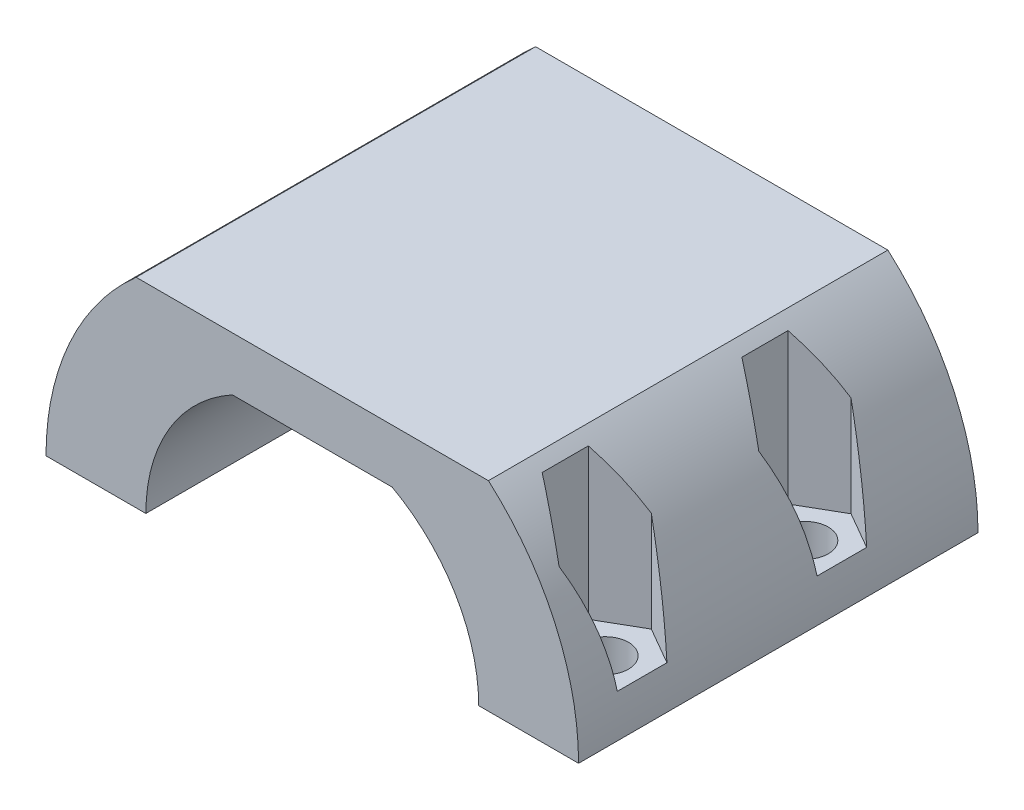
SolidWorks part; units mm, degrees
ref_plane "Front Plane" through (0, 0, 0) normal (0, 0, 1) x (1, 0, 0)
ref_plane "Top Plane" through (0, 0, 0) normal (0, 1, 0) x (1, 0, 0)
ref_plane "Right Plane" through (0, 0, 0) normal (1, 0, 0) x (0, 0, -1)
sketch "Sketch1" plane through (0, 0, 0) normal (0, 0, 1) x (1, 0, 0)
  line L0 (-20, 0) -> (-12.5, 0)
  line L1 (12.5, 0) -> (20, 0)
  line L2 (-6, 10.9659) -> (6, 10.9659)
  arc A0 (12.5, 0) -> (6, 10.9659) centre (0, 0) ccw
  arc A1 (20, 0) -> (-20, 0) centre (0, 0) ccw
  arc A2 (-6, 10.9659) -> (-12.5, 0) centre (0, 0) ccw
  dimension "D1" = 25
  dimension "D2" = 40
  dimension "D3" = 12
extrude "Boss-Extrude1" add sketch "Sketch1" along normal blind 30
sketch "Sketch2" plane through (0, 0, 0) normal (0, 1, 0) x (1, 0, 0)
  line L0 (0, 0) -> (0, -30) construction
  line L1 (-17, -25) -> (17, -25) construction
  line L2 (-17, -25) -> (-17, -10) construction
  line L3 (-17, -10) -> (17, -10) construction
  line L4 (17, -25) -> (17, -10) construction
  line L5 (-17, -25) -> (17, -10) construction
  line L6 (-17, -10) -> (17, -25) construction
  line L7 (-20, -30) -> (20, -30) construction
  line L8 (0, -30) -> (0, 0) construction
  circle A0 centre (-17, -10) radius 1.75
  circle A1 centre (17, -10) radius 1.75
  circle A2 centre (17, -25) radius 1.75
  circle A3 centre (-17, -25) radius 1.75
  point P0 (0, -17.5)
  dimension "D3" = 3.5
  dimension "D1" = 15
  dimension "D2" = 34
  dimension "D4" = 5
extrude "Cut-Extrude2" cut sketch "Sketch2" along normal through all
ref_plane "Plane1" through (0, 3, 0) normal (0, 1, 0) x (1, 0, 0)
sketch "Sketch4" plane through (0, 3, 0) normal (0, 1, 0) x (1, 0, 0)
  line L1 (-17, -6.5359) -> (-20, -8.2679)
  line L2 (-20, -8.2679) -> (-20, -11.7321)
  line L3 (-20, -11.7321) -> (-17, -13.4641)
  line L4 (-17, -13.4641) -> (-14, -11.7321)
  line L5 (-14, -11.7321) -> (-14, -8.2679)
  line L6 (-14, -8.2679) -> (-17, -6.5359)
  line L7 (-17, -21.5359) -> (-20, -23.2679)
  line L8 (-20, -23.2679) -> (-20, -26.7321)
  line L9 (-20, -26.7321) -> (-17, -28.4641)
  line L10 (-17, -28.4641) -> (-14, -26.7321)
  line L11 (-14, -26.7321) -> (-14, -23.2679)
  line L12 (-14, -23.2679) -> (-17, -21.5359)
  line L13 (17, -21.5359) -> (14, -23.2679)
  line L14 (14, -23.2679) -> (14, -26.7321)
  line L15 (14, -26.7321) -> (17, -28.4641)
  line L16 (17, -28.4641) -> (20, -26.7321)
  line L17 (20, -26.7321) -> (20, -23.2679)
  line L18 (20, -23.2679) -> (17, -21.5359)
  line L19 (14, -8.2679) -> (14, -11.7321)
  line L20 (14, -11.7321) -> (17, -13.4641)
  line L21 (17, -13.4641) -> (20, -11.7321)
  line L22 (20, -11.7321) -> (20, -8.2679)
  line L23 (20, -8.2679) -> (17, -6.5359)
  line L24 (17, -6.5359) -> (14, -8.2679)
  circle A1 centre (-17, -10) radius 3 construction
  circle A4 centre (-17, -25) radius 3 construction
  circle A6 centre (17, -25) radius 3 construction
  circle A7 centre (17, -10) radius 3 construction
  dimension "D1" = 6
extrude "Cut-Extrude3" cut sketch "Sketch4" along normal through all
sketch "Sketch5" plane through (0, 0, 30) normal (0, 0, 1) x (1, 0, 0)
  line L1 (-16.8059, 25) -> (16.8059, 25)
  line L2 (-16.8059, 25) -> (-16.8059, 15)
  line L3 (-16.8059, 15) -> (16.8059, 15)
  line L4 (16.8059, 25) -> (16.8059, 15)
  line L5 (-16.8059, 25) -> (16.8059, 15) construction
  line L6 (-16.8059, 15) -> (16.8059, 25) construction
  arc A0 (20, 0) -> (-20, 0) centre (0, 0) ccw construction
  point P0 (0, 20)
  dimension "10" = 10
extrude "Cut-Extrude4" cut sketch "Sketch5" against normal through all
